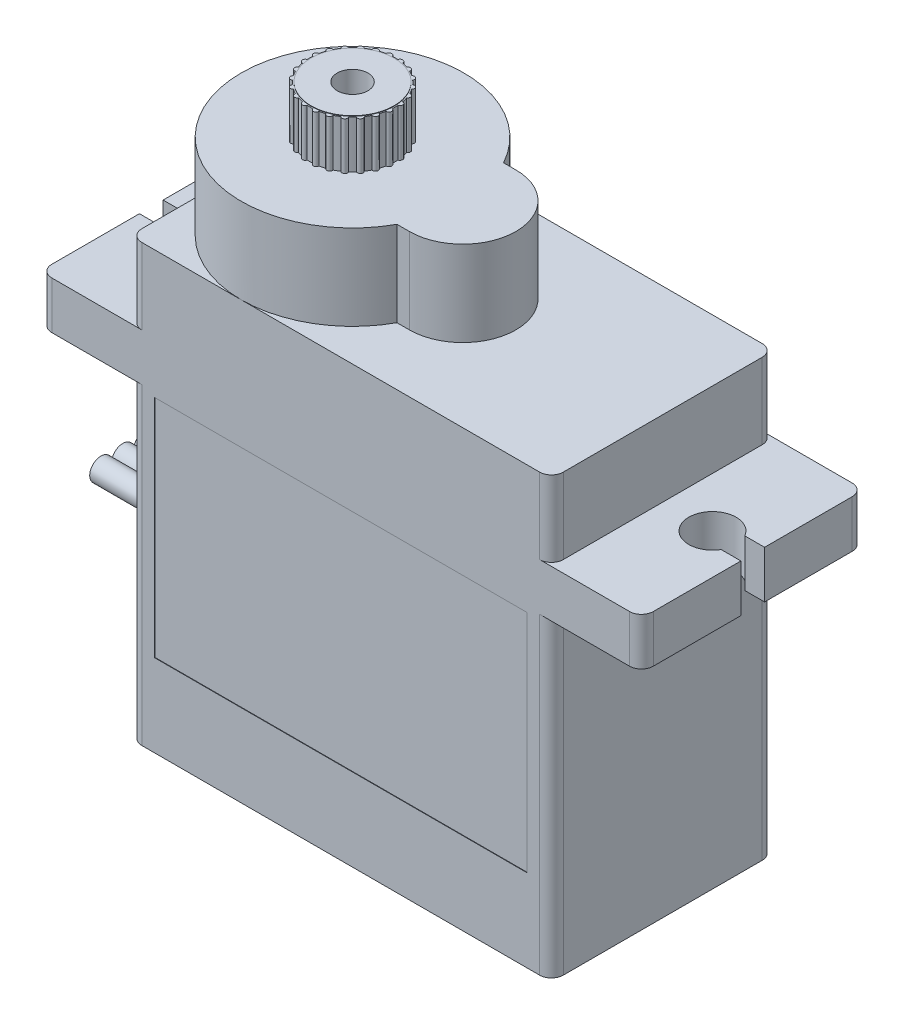
SolidWorks part; units mm, degrees
ref_plane "Front Plane" through (0, 0, 0) normal (0, 0, 1) x (1, 0, 0)
ref_plane "Top Plane" through (0, 0, 0) normal (0, 1, 0) x (1, 0, 0)
ref_plane "Right Plane" through (0, 0, 0) normal (1, 0, 0) x (0, 0, -1)
sketch "Sketch1" plane through (0, 0, 0) normal (0, 1, 0) x (1, 0, 0)
  line L1 (-11.303, -5.969) -> (11.303, -5.969)
  line L2 (-11.303, -5.969) -> (-11.303, 5.969)
  line L3 (-11.303, 5.969) -> (11.303, 5.969)
  line L4 (11.303, -5.969) -> (11.303, 5.969)
  line L5 (-11.303, -5.969) -> (11.303, 5.969) construction
  line L6 (-11.303, 5.969) -> (11.303, -5.969) construction
  point P0 (0, 0)
  dimension "D1" = 11.938
  dimension "D2" = 22.606
extrude "Boss-Extrude1" add sketch "Sketch1" along normal blind 23.368
sketch "Sketch3" plane through (0, 0, 0) normal (1, 0, 0) x (0, 0, -1)
  line L0 (-5.969, 23.368) -> (-5.969, 0) construction
  line L1 (-5.969, 16.764) -> (5.969, 16.764)
  line L2 (-5.969, 16.764) -> (-5.969, 19.304)
  line L3 (-5.969, 19.304) -> (5.969, 19.304)
  line L4 (5.969, 16.764) -> (5.969, 19.304)
  line L5 (5.969, 23.368) -> (5.969, 0) construction
  line L6 (-5.969, 0) -> (5.969, 0) construction
  dimension "D1" = 2.54
  dimension "D2" = 16.764
extrude "Boss-Extrude2" add sketch "Sketch3" along normal mid plane 32.258
sketch "Sketch4" plane through (0, 23.368, 0) normal (0, 1, 0) x (1, 0, 0)
  line L0 (-11.303, -5.969) -> (-11.303, 5.969) construction
  line L1 (-11.303, 0) -> (3.429, 0) construction
  line L2 (0.5715, 2.8575) -> (-0.0934, 2.8575)
  line L3 (0.5715, -2.8575) -> (-0.0934, -2.8575)
  arc A0 (-0.0934, 2.8575) -> (-0.0934, -2.8575) centre (-5.334, 0) ccw
  arc A1 (0.5715, -2.8575) -> (0.5715, 2.8575) centre (0.5715, 0) ccw
  dimension "D1" = 11.938
  dimension "D2" = 5.715
  dimension "D3" = 14.732
extrude "Boss-Extrude3" add sketch "Sketch4" along normal blind 4.572
sketch "Sketch5" plane through (0, 19.304, 0) normal (0, 1, 0) x (1, 0, 0)
  line L0 (16.129, 5.969) -> (16.129, -5.969) construction
  line L1 (16.129, 0.635) -> (16.129, -0.635)
  line L2 (16.129, 0) -> (12.7, 0) construction
  line L3 (16.129, 0.635) -> (15.0699, 0.635)
  line L4 (16.129, -0.635) -> (15.0699, -0.635)
  line L5 (0, 5.969) -> (0, -5.969) construction
  line L6 (11.303, 5.969) -> (-5.334, 5.969) construction
  line L7 (-5.334, -5.969) -> (11.303, -5.969) construction
  line L8 (16.129, 0.635) -> (15.0699, 0.635)
  line L9 (16.129, -0.635) -> (15.0699, -0.635)
  line L10 (-16.129, 0) -> (-12.7, 0) construction
  line L11 (-16.129, -0.635) -> (-15.0699, -0.635)
  line L12 (-16.129, 0.635) -> (-15.0699, 0.635)
  line L13 (-16.129, -0.635) -> (-15.0699, -0.635)
  line L14 (-16.129, 0.635) -> (-15.0699, 0.635)
  line L15 (-16.129, 0.635) -> (-16.129, -0.635)
  line L16 (-12.7, 0) -> (12.7, 0) construction
  arc A0 (15.0699, 0.635) -> (15.0699, -0.635) centre (13.97, 0) ccw
  arc A1 (-15.0699, 0.635) -> (-15.0699, -0.635) centre (-13.97, 0) cw
  point P2 (16.129, 0.635)
  point P3 (16.129, -0.635)
  point P12 (16.129, 0.635)
  point P22 (16.129, -0.635)
  point P31 (-16.129, -0.635)
  point P32 (-16.129, 0.635)
  point P33 (-16.129, -0.635)
  point P34 (-16.129, 0.635)
  line M8 (16.129, -5.969) -> (16.129, 5.969)
  dimension "D1" = 2.54
  dimension "D2" = 5.334
  dimension "D3" = 5.334
  dimension "D4" = 25.4
extrude "Cut-Extrude1" cut sketch "Sketch5" against normal through all both and the other way through all contours A1 L12 L15 L11 | L3 A0 L4 M8
sketch "Sketch6" plane through (0, 27.94, 0) normal (0, 1, 0) x (1, 0, 0)
  circle A0 centre (-5.334, 0) radius 2.413
  circle A1 centre (-5.334, 0) radius 2.286
  circle A2 centre (-5.334, 0) radius 0.8255
  dimension "D1" = 4.826
  dimension "D2" = 4.572
  dimension "D3" = 1.651
extrude "Boss-Extrude4" add sketch "Sketch6" along normal offset from surface (2.54 mm away) 30.48 contours A0 A1 | A1 A2 up to face at (0, 0, 0)
sketch "Sketch8" plane through (0, 30.48, 0) normal (0, 1, 0) x (1, 0, 0)
  line L0 (-5.334, 2.286) -> (-5.334, 2.413) construction
  line L1 (-5.334, 0) -> (-5.019, 2.3924) construction
  line L2 (-5.1845, 2.2811) -> (-5.334, 0) construction
  arc A0 (-5.019, 2.3924) -> (-5.1845, 2.2811) centre (-5.0387, 2.243) ccw
  circle A1 centre (-5.334, 0) radius 0.8255
  circle A2 centre (-5.334, 0) radius 0.8255 construction
  circle A3 centre (-5.334, 0) radius 2.286
  circle A4 centre (-5.334, 0) radius 2.286
  circle A5 centre (-5.334, 0) radius 2.413
  circle A6 centre (-5.334, 0) radius 2.413
  arc A7 (-5.649, 2.3924) -> (-5.4835, 2.2811) centre (-5.6293, 2.243) cw
  arc A8 (-5.019, 2.3924) -> (-4.888, 2.2421) centre (-5.0387, 2.243) cw
  arc A9 (-4.4106, 2.2293) -> (-4.5992, 2.1647) centre (-4.4683, 2.0901) ccw
  arc A10 (-4.4106, 2.2293) -> (-4.3229, 2.0503) centre (-4.4683, 2.0901) cw
  arc A11 (-3.8651, 1.9144) -> (-4.064, 1.9007) centre (-3.9568, 1.7948) ccw
  arc A12 (-3.8651, 1.9144) -> (-3.8267, 1.7187) centre (-3.9568, 1.7948) cw
  arc A13 (-3.4196, 1.4689) -> (-3.6153, 1.5073) centre (-3.5392, 1.3772) ccw
  arc A14 (-3.4196, 1.4689) -> (-3.4333, 1.27) centre (-3.5392, 1.3772) cw
  arc A15 (-3.1047, 0.9234) -> (-3.2837, 1.0111) centre (-3.2439, 0.8657) ccw
  arc A16 (-3.1047, 0.9234) -> (-3.1693, 0.7348) centre (-3.2439, 0.8657) cw
  arc A17 (-2.9416, 0.315) -> (-3.0919, 0.446) centre (-3.091, 0.2953) ccw
  arc A18 (-2.9416, 0.315) -> (-3.0529, 0.1495) centre (-3.091, 0.2953) cw
  arc A19 (-2.9416, -0.315) -> (-3.0529, -0.1495) centre (-3.091, -0.2953) ccw
  arc A20 (-2.9416, -0.315) -> (-3.0919, -0.446) centre (-3.091, -0.2953) cw
  arc A21 (-3.1047, -0.9234) -> (-3.1693, -0.7348) centre (-3.2439, -0.8657) ccw
  arc A22 (-3.1047, -0.9234) -> (-3.2837, -1.0111) centre (-3.2439, -0.8657) cw
  arc A23 (-3.4196, -1.4689) -> (-3.4333, -1.27) centre (-3.5392, -1.3772) ccw
  arc A24 (-3.4196, -1.4689) -> (-3.6153, -1.5073) centre (-3.5392, -1.3772) cw
  arc A25 (-3.8651, -1.9144) -> (-3.8267, -1.7187) centre (-3.9568, -1.7948) ccw
  arc A26 (-3.8651, -1.9144) -> (-4.064, -1.9007) centre (-3.9568, -1.7948) cw
  arc A27 (-4.4106, -2.2293) -> (-4.3229, -2.0503) centre (-4.4683, -2.0901) ccw
  arc A28 (-4.4106, -2.2293) -> (-4.5992, -2.1647) centre (-4.4683, -2.0901) cw
  arc A29 (-5.019, -2.3924) -> (-4.888, -2.2421) centre (-5.0387, -2.243) ccw
  arc A30 (-5.019, -2.3924) -> (-5.1845, -2.2811) centre (-5.0387, -2.243) cw
  arc A31 (-5.649, -2.3924) -> (-5.4835, -2.2811) centre (-5.6293, -2.243) ccw
  arc A32 (-5.649, -2.3924) -> (-5.78, -2.2421) centre (-5.6293, -2.243) cw
  arc A33 (-6.2574, -2.2293) -> (-6.0688, -2.1647) centre (-6.1997, -2.0901) ccw
  arc A34 (-6.2574, -2.2293) -> (-6.3451, -2.0503) centre (-6.1997, -2.0901) cw
  arc A35 (-6.8029, -1.9144) -> (-6.604, -1.9007) centre (-6.7112, -1.7948) ccw
  arc A36 (-6.8029, -1.9144) -> (-6.8413, -1.7187) centre (-6.7112, -1.7948) cw
  arc A37 (-7.2484, -1.4689) -> (-7.0527, -1.5073) centre (-7.1288, -1.3772) ccw
  arc A38 (-7.2484, -1.4689) -> (-7.2347, -1.27) centre (-7.1288, -1.3772) cw
  arc A39 (-7.5633, -0.9234) -> (-7.3843, -1.0111) centre (-7.4241, -0.8657) ccw
  arc A40 (-7.5633, -0.9234) -> (-7.4987, -0.7348) centre (-7.4241, -0.8657) cw
  arc A41 (-7.7264, -0.315) -> (-7.5761, -0.446) centre (-7.577, -0.2953) ccw
  arc A42 (-7.7264, -0.315) -> (-7.6151, -0.1495) centre (-7.577, -0.2953) cw
  arc A43 (-7.7264, 0.315) -> (-7.6151, 0.1495) centre (-7.577, 0.2953) ccw
  arc A44 (-7.7264, 0.315) -> (-7.5761, 0.446) centre (-7.577, 0.2953) cw
  arc A45 (-7.5633, 0.9234) -> (-7.4987, 0.7348) centre (-7.4241, 0.8657) ccw
  arc A46 (-7.5633, 0.9234) -> (-7.3843, 1.0111) centre (-7.4241, 0.8657) cw
  arc A47 (-7.2484, 1.4689) -> (-7.2347, 1.27) centre (-7.1288, 1.3772) ccw
  arc A48 (-7.2484, 1.4689) -> (-7.0527, 1.5073) centre (-7.1288, 1.3772) cw
  arc A49 (-6.8029, 1.9144) -> (-6.8413, 1.7187) centre (-6.7112, 1.7948) ccw
  arc A50 (-6.8029, 1.9144) -> (-6.604, 1.9007) centre (-6.7112, 1.7948) cw
  arc A51 (-6.2574, 2.2293) -> (-6.3451, 2.0503) centre (-6.1997, 2.0901) ccw
  arc A52 (-6.2574, 2.2293) -> (-6.0688, 2.1647) centre (-6.1997, 2.0901) cw
  arc A53 (-5.649, 2.3924) -> (-5.78, 2.2421) centre (-5.6293, 2.243) ccw
  point P157 (-5.334, 0)
  circle M8 centre (-5.334, 0) radius 2.413
  dimension "D4" = 7.5
  dimension "D5" = 3.75
  dimension "D1" = 0
  dimension "D2" = 0
  dimension "D3" = 0
  dimension "D6" = 24
extrude "Cut-Extrude2" cut sketch "Sketch8" against normal up to surface (2.54 mm away) contours A49 A48 A4 M8 | A47 A46 A4 M8 | A45 A44 A4 M8 | A43 A42 A4 M8 | A41 A40 A4 M8 | A39 A38 A4 M8 | A37 A36 A4 M8 | A35 A34 A4 M8 | A33 A32 A4 M8 | A31 A30 A4 M8 | A29 A28 A4 M8 | A27 A26 A4 M8 | A25 A24 A4 M8 | A23 A22 A4 M8 | A21 A20 A4 M8 | A19 A18 A4 M8 | A17 A16 A4 M8 | A15 A14 A4 M8 | A13 A12 A4 M8 | A11 A10 A4 M8 | A9 A8 A4 M8 | A7 A4 A0 M8 | A53 A6 A52 A4 | A51 A50 A4 M8 up to face at (-5.334, 27.94, 2.413)
sketch "Sketch9" plane through (0, 30.48, 0) normal (0, 1, 0) x (1, 0, 0)
  circle A0 centre (-5.334, 0) radius 2.2225
  circle A1 centre (-5.334, 0) radius 0.8255
  circle A2 centre (-5.334, 0) radius 0.8255
  dimension "D2" = 4.445
  dimension "D1" = 0
extrude "Boss-Extrude5" add sketch "Sketch9" along normal blind 0.0254
fillet "Fillet1" radius 0.635 8 edges at (-11.303, 8.382, -5.969) (-11.303, 21.336, -5.969) (-11.303, 21.336, 5.969) (-11.303, 8.382, 5.969) (11.303, 8.382, -5.969) (11.303, 8.382, 5.969) (11.303, 21.336, -5.969) (11.303, 21.336, 5.969)
fillet "Fillet2" radius 0.635 4 edges at (-16.129, 18.034, -5.969) (16.129, 18.034, -5.969) (16.129, 18.034, 5.969) (-16.129, 18.034, 5.969)
sketch "Sketch10" plane through (0, 0, 0) normal (0, -1, 0) x (1, 0, 0)
  line L0 (-10.668, 5.969) -> (10.668, 5.969) construction
  line L1 (-11.303, -5.334) -> (-11.303, 5.334) construction
  line L2 (-11.303, 0) -> (11.303, 0) construction
  line L3 (11.303, 5.334) -> (11.303, -5.334) construction
  line L5 (0, 5.969) -> (0, -5.969) construction
  line L6 (10.668, -5.969) -> (-10.668, -5.969) construction
  circle A0 centre (-10.16, 4.826) radius 0.9842
  circle A1 centre (-10.16, -4.826) radius 0.9842
  circle A2 centre (10.16, -4.826) radius 0.9842
  circle A3 centre (10.16, 4.826) radius 0.9842
  dimension "D1" = 1.9685
  dimension "D2" = 1.143
  dimension "D3" = 1.143
extrude "Cut-Extrude3" cut sketch "Sketch10" against normal blind 2.54
sketch "Sketch11" plane through (-11.303, 0, 0) normal (-1, 0, 0) x (0, 0, 1)
  line L0 (-1.778, 6.35) -> (1.778, 6.35)
  line L1 (0, 0) -> (0, 6.35) construction
  line L2 (-5.334, 0) -> (5.334, 0) construction
  line L3 (-1.778, 6.35) -> (-1.778, 7.5565)
  line L4 (-1.778, 7.5565) -> (1.778, 7.5565)
  line L5 (1.778, 7.5565) -> (1.778, 6.35)
  circle A0 centre (-1.1747, 6.9532) radius 0.6033
  circle A1 centre (0, 6.9532) radius 0.6033
  circle A2 centre (1.1747, 6.9532) radius 0.6033
  dimension "D1" = 6.35
  dimension "D2" = 3.556
  dimension "D3" = 1.2065
extrude "Boss-Extrude7" add sketch "Sketch11" along normal blind 6.35 contours A1 A0 | A2 A1 A0 | A2 A1 | A0 A1 | A1 A2
sketch "Sketch13" plane through (0, 0, 5.969) normal (0, 0, 1) x (1, 0, 0)
  line L0 (-10.668, 0) -> (10.668, 0) construction
  line L1 (-9.9949, 4.4196) -> (9.9949, 4.4196)
  line L2 (-9.9949, 4.4196) -> (-9.9949, 16.51)
  line L3 (-9.9949, 16.51) -> (9.9949, 16.51)
  line L4 (9.9949, 4.4196) -> (9.9949, 16.51)
  line L5 (-9.9949, 4.4196) -> (9.9949, 16.51) construction
  line L6 (-9.9949, 16.51) -> (9.9949, 4.4196) construction
  point P0 (0, 10.4648)
  dimension "D1" = 12.0904
  dimension "D2" = 16.51
  dimension "D3" = 19.9898
extrude "Cut-Extrude4" cut sketch "Sketch13" against normal blind 0.0254
